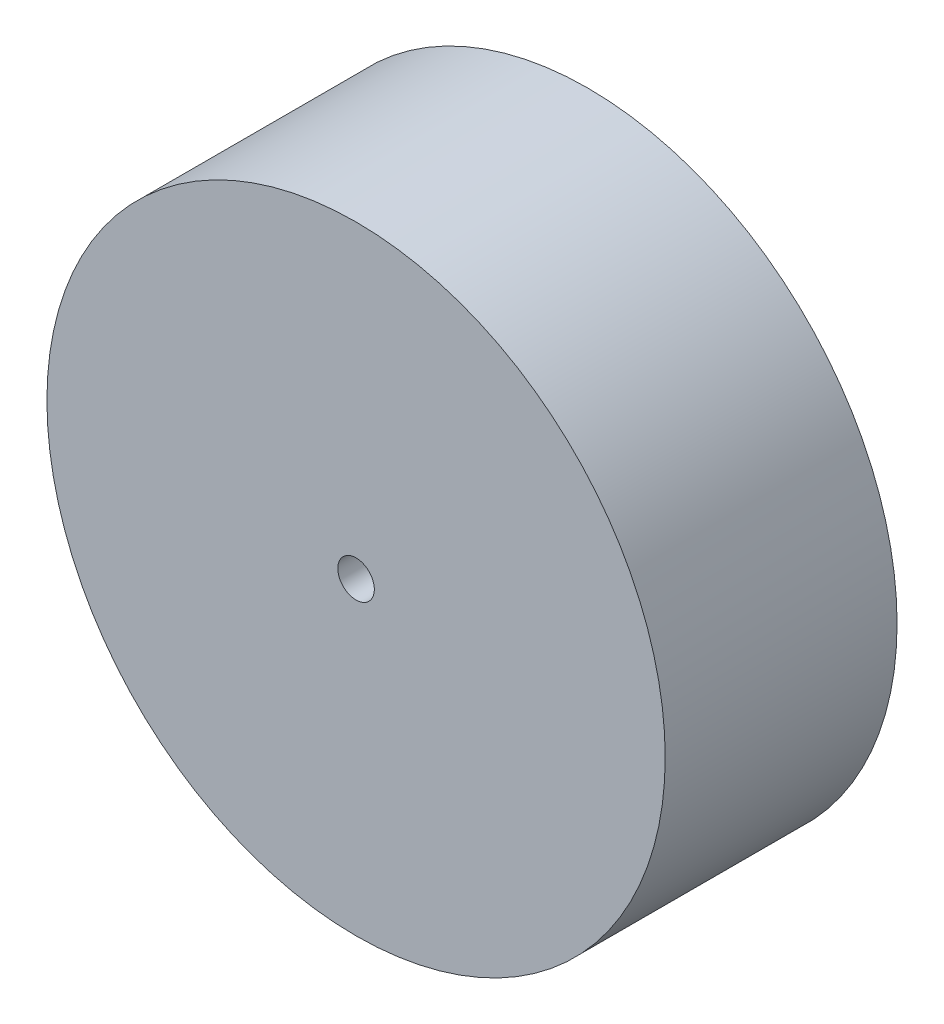
SolidWorks part; units mm, degrees
ref_plane "Front Plane" through (0, 0, 0) normal (0, 0, 1) x (1, 0, 0)
ref_plane "Top Plane" through (0, 0, 0) normal (0, 1, 0) x (1, 0, 0)
ref_plane "Right Plane" through (0, 0, 0) normal (1, 0, 0) x (0, 0, -1)
sketch "Sketch4" plane through (0, 0, 0) normal (0, 0, 1) x (1, 0, 0)
  circle A0 centre (0, 0) radius 25.4
  circle A1 centre (0, 0) radius 1.5
extrude "Boss-Extrude4" add sketch "Sketch4" along normal blind 19.05 contours A0
sketch "Sketch6" plane through (0, 0, 0) normal (0, 0, -1) x (-1, 0, 0)
  circle A0 centre (0, 0) radius 1.5
extrude "Cut-Extrude1" cut sketch "Sketch6" against normal blind 19.05
